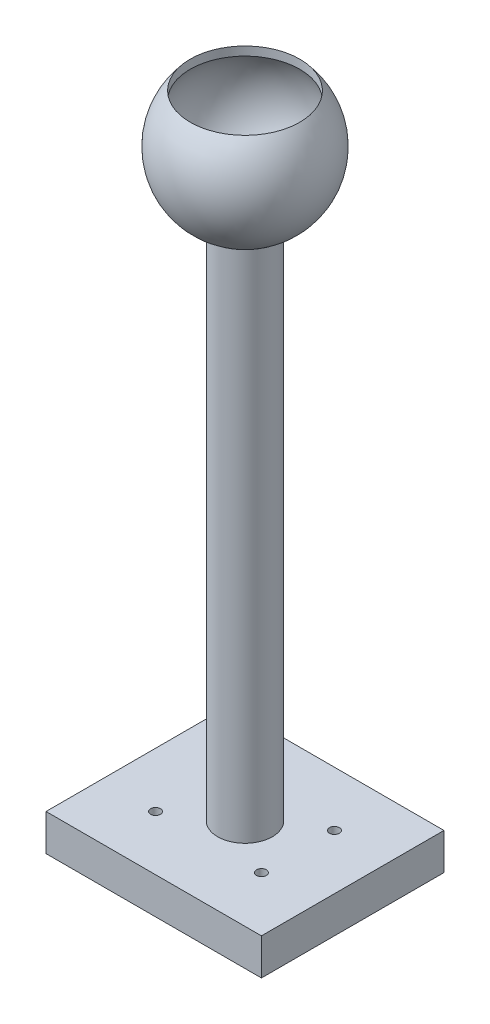
SolidWorks part; units mm, degrees
ref_plane "Alzado" through (0, 0, 0) normal (0, 0, 1) x (1, 0, 0)
ref_plane "Planta" through (0, 0, 0) normal (0, 1, 0) x (1, 0, 0)
ref_plane "Vista lateral" through (0, 0, 0) normal (1, 0, 0) x (0, 0, -1)
sketch "Croquis1" plane through (0, 0, 0) normal (0, 1, 0) x (1, 0, 0)
  line L1 (-29.5, -25) -> (29.5, -25)
  line L2 (-29.5, -25) -> (-29.5, 25)
  line L3 (-29.5, 25) -> (29.5, 25)
  line L4 (29.5, -25) -> (29.5, 25)
  line L5 (-29.5, -25) -> (29.5, 25) construction
  line L6 (-29.5, 25) -> (29.5, -25) construction
  point P0 (0, 0)
  dimension "D1" = 59
  dimension "D2" = 50
extrude "Saliente-Extruir1 50X50X24" add sketch "Croquis1" along normal blind 24
sketch "Croquis2" plane through (0, 24, 0) normal (0, 1, 0) x (1, 0, 0)
  circle A0 centre (0, 0) radius 7.5
  dimension "D1" = 15
extrude "Saliente-Extruir2 15MM" add sketch "Croquis2" along normal blind 160
sketch "Croquis3" plane through (0, 184, 0) normal (0, 1, 0) x (1, 0, 0)
  line L0 (0, 20) -> (0, -20)
  arc A0 (0, -20) -> (0, 20) centre (0, 0) ccw
  dimension "D1" = 40
revolve "Revolución2 40 MM" add sketch "Croquis3" angle 360 about L0
ref_plane "Plano1" through (0, 184, 0) normal (0, 1, 0) x (1, 0, 0)
sketch "Croquis6" plane through (0, 184, 0) normal (0, 1, 0) x (1, 0, 0)
  line L0 (0, 18.5) -> (0, -18.5)
  arc A0 (0, -18.5) -> (0, 18.5) centre (0, 0) ccw
  dimension "D1" = 37
sketch "Croquis8" plane through (0, 24, 0) normal (0, 1, 0) x (1, 0, 0)
  line L0 (29.5, 25) -> (-29.5, 25) construction
  line L1 (-29.5, 25) -> (-29.5, -25) construction
  line L2 (0, 21.2829) -> (0, 0) construction
  line L3 (0, 0) -> (21.4594, 0) construction
  circle A0 centre (-14.5, 10) radius 1.35
  circle A1 centre (14.5, 10) radius 1.35
  circle A2 centre (14.5, -10) radius 1.35
  circle A3 centre (-14.5, -10) radius 1.35
  dimension "D1" = 2.7
  dimension "D2" = 15
  dimension "D3" = 15
extrude "EXTRUIR TORNILLOS 2.7MM" cut sketch "Croquis8" against normal blind 25
revolve "EXTRUIR CENTRO CIRCULO 37 MM" cut sketch "Croquis6" angle 360 about L0
sketch "Croquis10" plane through (0, 184, 0) normal (0, 1, 0) x (1, 0, 0)
  circle A0 centre (0, 0) radius 15
  dimension "D1" = 30
extrude "EXTRUIR ARRIBA 30 MM" cut sketch "Croquis10" along normal blind 29
sketch "MEDIDA ALTURA 197.24" plane through (0, 0, 0) normal (0, 0, 1) x (1, 0, 0)
  line L0 (-9.8146, 197.2288) -> (52.6281, 197.2288) construction
  line L2 (19.7342, 0) -> (69.9113, 0) construction
  line L3 (-29.5, 0) -> (29.5, 0) construction
  dimension "D1" = 197.2288
sketch "184MM" plane through (0, 0, 0) normal (0, 0, 1) x (1, 0, 0)
  line L0 (0, 184) -> (0, 0) construction
  line L1 (18.5, 184) -> (0, 184) construction
  line L2 (-29.5, 0) -> (29.5, 0) construction
  line L3 (-38.3353, 0) -> (38.3353, 0)
  line L4 (-38.3353, 0) -> (-38.3353, 14)
  line L5 (-38.3353, 14) -> (38.3353, 14)
  line L6 (38.3353, 0) -> (38.3353, 14)
  line L7 (-38.3353, 0) -> (38.3353, 14) construction
  line L8 (-38.3353, 14) -> (38.3353, 0) construction
  point P5 (0, 7)
  dimension "D1" = 184
  dimension "D2" = 170
extrude "Cortar-Extruir1" cut sketch "184MM" against normal blind 40 and the other way blind 40
